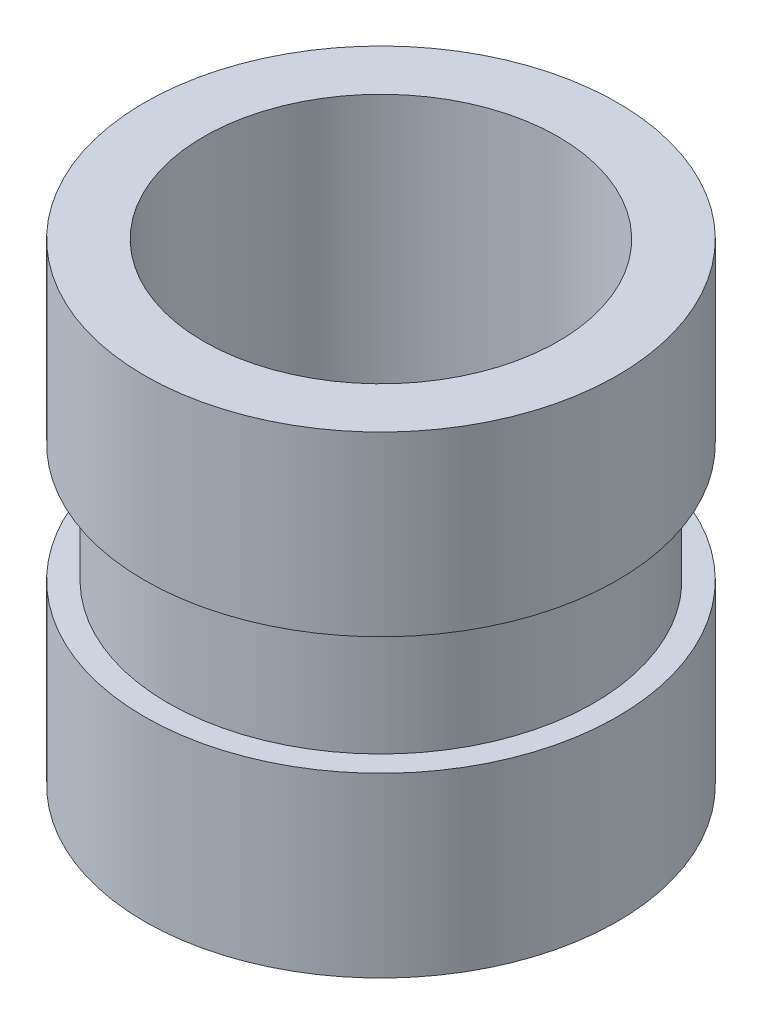
SolidWorks part; units mm, degrees
ref_plane "Front Plane" through (0, 0, 0) normal (0, 0, 1) x (1, 0, 0)
ref_plane "Top Plane" through (0, 0, 0) normal (0, 1, 0) x (1, 0, 0)
ref_plane "Right Plane" through (0, 0, 0) normal (1, 0, 0) x (0, 0, -1)
sketch "Sketch1" plane through (0, 0, 0) normal (0, 0, 1) x (1, 0, 0)
  line L0 (1.5, 0) -> (2, 0)
  line L1 (2, 0) -> (2, 1.5)
  line L2 (2, 1.5) -> (1.8, 1.5)
  line L3 (1.8, 1.5) -> (1.8, 2.5)
  line L4 (1.8, 2.5) -> (2, 2.5)
  line L5 (2, 2.5) -> (2, 4)
  line L6 (2, 4) -> (1.5, 4)
  line L7 (1.5, 4) -> (1.5, 0)
  line L8 (0, 4.902) -> (0, -1.8868) construction
  dimension "D1" = 1.5
  dimension "D2" = 1.5
  dimension "D3" = 4
  dimension "D4" = 0.2
  dimension "D5" = 1.5
  dimension "D6" = 2
revolve "Revolve1" add sketch "Sketch1" angle 360 about L8
